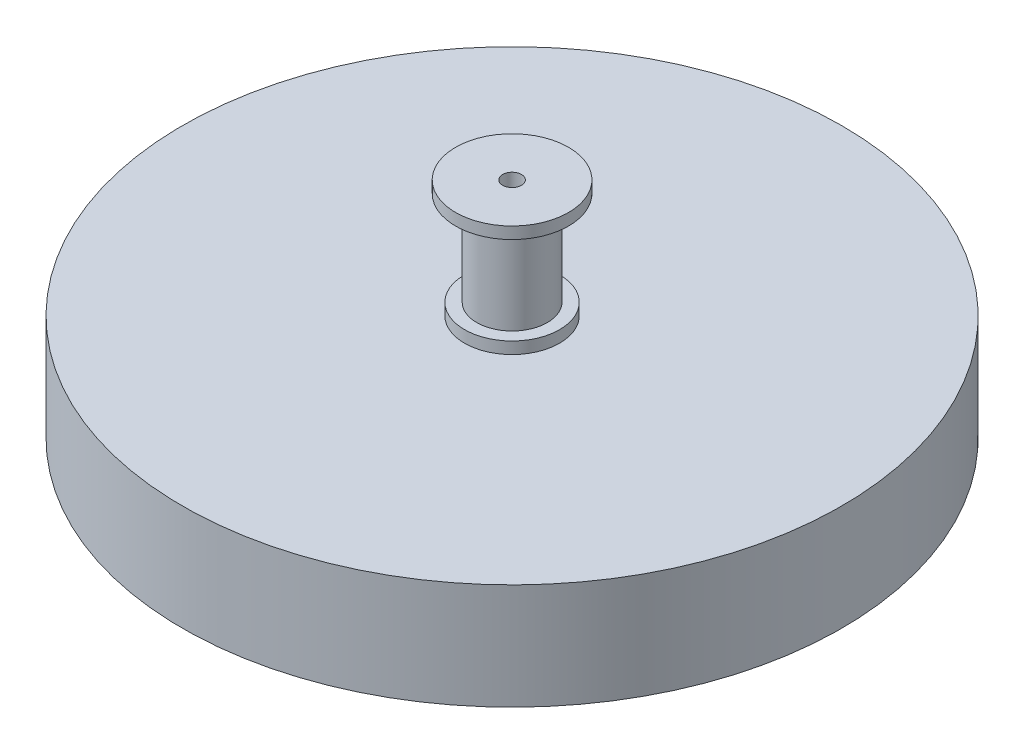
SolidWorks part; units mm, degrees
material "AISI 304"
ref_plane "Front Plane" through (0, 0, 0) normal (0, 0, 1) x (1, 0, 0)
ref_plane "Top Plane" through (0, 0, 0) normal (0, 1, 0) x (1, 0, 0)
ref_plane "Right Plane" through (0, 0, 0) normal (1, 0, 0) x (0, 0, -1)
sketch "Sketch1" plane through (0, 0, 0) normal (1, 0, 0) x (0, 0, -1)
  line L0 (0, -1004.7126) -> (0, 49230.9178) construction
  line L1 (-1004.7126, 0) -> (49230.9178, 0) construction
  line L3 (-24, 72.5) -> (-24, 67.5)
  line L4 (-24, 67.5) -> (-15, 67.5)
  line L5 (-15, 67.5) -> (-15, 27.5)
  line L6 (-15, 27.5) -> (-20.1905, 27.5)
  line L7 (-20.1905, 27.5) -> (-20.1905, 22.5)
  line L8 (-20.1905, 22.5) -> (-140, 22.5)
  line L9 (-140, 22.5) -> (-140, -22.5)
  line L10 (-140, -22.5) -> (-20.1905, -22.5)
  line L15 (-24, 72.5) -> (-4, 72.5)
  line L19 (-4, -32.5) -> (-4, 72.5)
  line L20 (-20.1905, -27.5) -> (-20.1905, -22.5)
  line L21 (-15, -27.5) -> (-20.1905, -27.5)
  line L22 (-15, -67.5) -> (-15, -27.5)
  line L23 (-24, -67.5) -> (-15, -67.5)
  line L24 (-24, -72.5) -> (-24, -67.5)
  line L25 (-24, -72.5) -> (-4, -72.5)
  line L26 (-4, -72.5) -> (-4, -32.5)
  point P7 (-140, 0)
  point P24 (0, 0)
  dimension "D2" = 20
  dimension "D3" = 40
  dimension "D4" = 5
  dimension "D5" = 5
  dimension "D6" = 45
  dimension "D8" = 30
  dimension "D9" = 8
  dimension "D10" = 5
  dimension "D11" = 140
revolve "Revolve1" add sketch "Sketch1" angle 360 about L0
